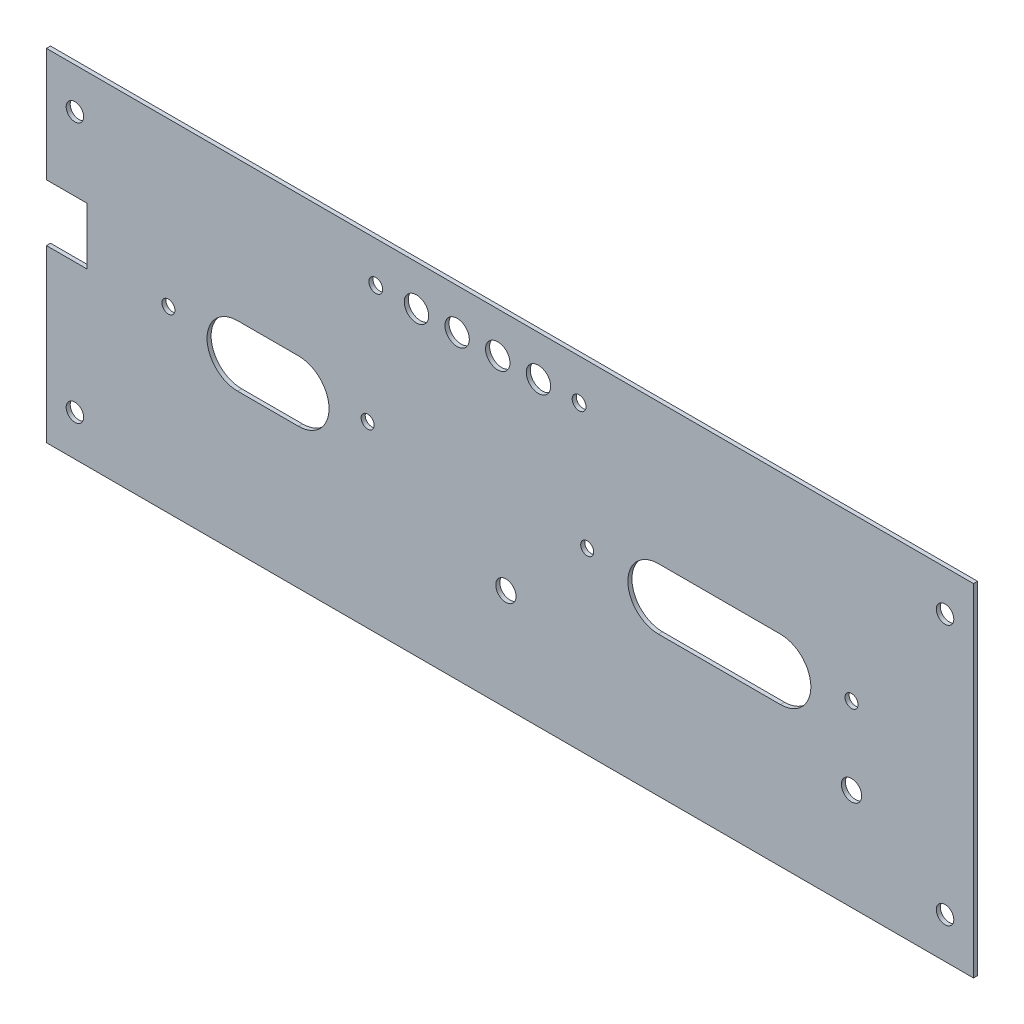
SolidWorks part; units mm, degrees
ref_plane "Спереди" through (0, 0, 0) normal (0, 0, 1) x (1, 0, 0)
ref_plane "Сверху" through (0, 0, 0) normal (0, 1, 0) x (1, 0, 0)
ref_plane "Справа" through (0, 0, 0) normal (1, 0, 0) x (0, 0, -1)
sketch "Эскиз1" plane through (0, 0, 0) normal (0, 0, 1) x (1, 0, 0)
  line L0 (0, 0) -> (58.061, 0) construction
  line L1 (0, 0) -> (0, 47.3035) construction
  line L3 (-114, -42) -> (114, -42)
  line L4 (-114, -42) -> (-114, 42)
  line L5 (-114, 42) -> (114, 42)
  line L6 (114, -42) -> (114, 42)
  circle A8 centre (107, 32) radius 2.15
  circle A9 centre (-107, 32) radius 2.15
  circle A10 centre (-107, -32) radius 2.15
  circle A11 centre (107, -32) radius 2.15
  dimension "D14" = 4.3
  dimension "D15" = 10
  dimension "D16" = 7
  dimension "D1" = 84
  dimension "D2" = 228
extrude "Вытянуть1" add sketch "Эскиз1" along normal blind 1
sketch "Эскиз4" plane through (0, 0, 1) normal (0, 0, 1) x (1, 0, 0)
  line L0 (-114, 42) -> (-114, -42) construction
  line L1 (-114, -42) -> (114, -42) construction
  line L2 (-95.842, 0) -> (24.8302, 0) construction
  line L3 (36.5, 7.5) -> (66.5, 7.5)
  line L4 (36.5, -7.5) -> (66.5, -7.5)
  line L5 (51.5, -2.1564) -> (51.5, -32.5755) construction
  line L6 (-67, 7.5) -> (-52, 7.5)
  line L7 (-67, -7.5) -> (-52, -7.5)
  line L8 (-59.5, -4.8658) -> (-59.5, -32.5755) construction
  line L9 (19, 2) -> (84, 2) construction
  line L10 (0, 76.9526) -> (0, -67.5216) construction
  line L11 (114, -42) -> (114, 42) construction
  line L13 (-118.4641, 0) -> (-104, 0)
  line L14 (-118.4641, 0) -> (-118.4641, 14)
  line L15 (-118.4641, 14) -> (-104, 14)
  line L16 (-104, 0) -> (-104, 14)
  arc A1 (36.5, 7.5) -> (36.5, -7.5) centre (36.5, 0) ccw
  arc A2 (66.5, 7.5) -> (66.5, -7.5) centre (66.5, 0) cw
  circle A3 centre (19, 2) radius 1.6
  circle A4 centre (84, 2) radius 1.6
  arc A5 (-67, 7.5) -> (-67, -7.5) centre (-67, 0) ccw
  arc A6 (-52, 7.5) -> (-52, -7.5) centre (-52, 0) cw
  circle A7 centre (-84, 2) radius 1.6
  circle A8 centre (-35, 2) radius 1.6
  dimension "D3" = 14
  dimension "D6" = 15
  dimension "D5" = 30
  dimension "D8" = 2
  dimension "D4" = 42
  dimension "D9" = 3.2
  dimension "D7" = 32.5
  dimension "D12" = 30
  dimension "D13" = 15
  dimension "D14" = 49
  dimension "D15" = 2
  dimension "D11" = 32.5
  dimension "D10" = 30
  dimension "D2" = 10
  dimension "D16" = 15
  dimension "D17" = 42
extrude "Вырез-Вытянуть2" cut sketch "Эскиз4" against normal blind 1
sketch "Эскиз5" plane through (0, 0, 1) normal (0, 0, 1) x (1, 0, 0)
  line L0 (-8, 37.0344) -> (-8, 0) construction
  line L1 (-33, 32) -> (17, 32) construction
  line L2 (-56.6851, -17) -> (72.361, -17) construction
  line L3 (84, 2) -> (84, -27.7356) construction
  line L4 (-114, -42) -> (114, -42) construction
  circle A0 centre (-33, 32) radius 1.7
  circle A1 centre (17, 32) radius 1.7
  circle A2 centre (-35, 2) radius 1.6 construction
  circle A3 centre (19, 2) radius 1.6 construction
  circle A4 centre (7, 32) radius 3
  circle A5 centre (-3, 32) radius 3
  circle A6 centre (-13, 32) radius 3
  circle A7 centre (-23, 32) radius 3
  circle A8 centre (-1, -17) radius 2.5
  circle A9 centre (84, -17) radius 2.5
  circle A10 centre (27, 32) radius 3 [skipped]
  circle A11 centre (-43, 32) radius 3 [skipped]
  circle A12 centre (17, 32) radius 3 [skipped]
  circle A13 centre (-33, 32) radius 3 [skipped]
  dimension "D1" = 50
  dimension "D2" = 3.4
  dimension "D5" = 30
  dimension "D6" = 6
  dimension "D7" = 85
  dimension "D8" = 5
  dimension "D3" = 74
  dimension "D4" = 25
extrude "Вырез-Вытянуть3" cut sketch "Эскиз5" against normal blind 10
